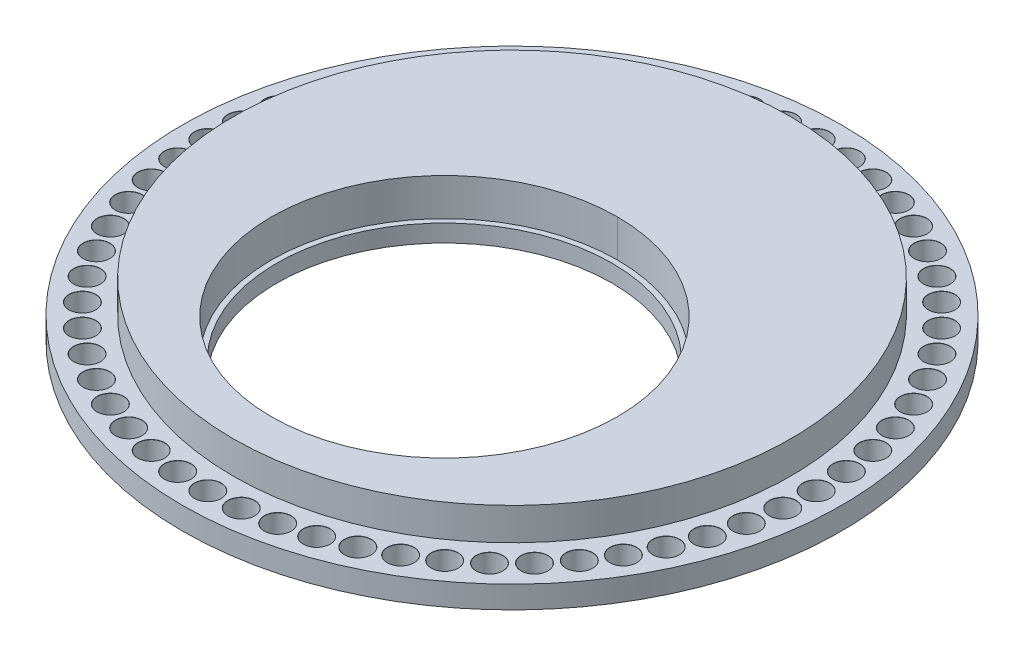
SolidWorks part; units mm, degrees
material "6061-T6 (SS)"
ref_plane "X-Y Datum" through (0, 0, 0) normal (0, 0, 1) x (1, 0, 0)
ref_plane "X-Z Datum" through (0, 0, 0) normal (0, 1, 0) x (1, 0, 0)
ref_plane "Y-Z Datum" through (0, 0, 0) normal (1, 0, 0) x (0, 0, -1)
sketch "Sketch1" plane through (0, 0, 0) normal (0, 1, 0) x (1, 0, 0)
  line L0 (0, 0) -> (0, -12.7) construction
  line L1 (0, -43.0151) -> (0, 43.0151) construction
  line L2 (0, 52.3875) -> (0, 61.9125) construction
  circle A0 centre (0, -12.7) radius 30.988
  circle A1 centre (0, 0) radius 52.3875 construction
  circle A2 centre (0, 0) radius 61.9125
  circle A3 centre (0, 0) radius 57.15 construction
  point P12 (0, 57.15)
  dimension "D2" = 61.976
  dimension "D3" = 104.775
  dimension "D4" = 123.825
  dimension "D5" = 114.3
  dimension "D1" = 12.7
extrude "Slotted-Body Extrude" add sketch "Sketch1" along normal blind 4.191
sketch "Sketch5" plane through (0, 4.191, 0) normal (0, 1, 0) x (1, 0, 0)
  circle A0 centre (0, 0) radius 52.3875 construction
  circle A1 centre (0, 0) radius 52.3875
extrude "Boss-Extrude3" add sketch "Sketch5" along normal blind 6.08
sketch "Sketch6" plane through (0, 0, 0) normal (0, -1, 0) x (1, 0, 0)
  line L0 (0, 73.8452) -> (0, -27.2688) construction
  line L1 (0, -27.2688) -> (0, -30.4713) construction
  line L2 (0, -30.4713) -> (0, -33.9346) construction
  line L3 (0, -46.4199) -> (0, -77.5412) construction
  circle A0 centre (0, 12.7) radius 30.988 construction
  circle A1 centre (0, 12.7) radius 30.988 construction
  circle A2 centre (0, 12.7) radius 32.512
  point P30 (0, 0)
  point P32 (0, 0)
  dimension "D1" = 65.024
extrude "Cut-Extrude5" cut sketch "Sketch6" against normal through all
sketch "Sketch8" plane through (0, 0, 0) normal (0, -1, 0) x (1, 0, 0)
  circle A0 centre (0, 12.7) radius 32.512 construction
  circle A1 centre (0, 12.7) radius 32.512
  circle A2 centre (0, 12.7) radius 31.496
  dimension "D1" = 62.992
extrude "Boss-Extrude4" add sketch "Sketch8" against normal blind 3.255 separate body
hole_wizard "Ø5.0mm Dowel Hole1" positions "Sketch9" profile "Sketch10" hole size "Ø5.0" standard "ANSI Metric" end condition through all
sketch "Sketch9" plane through (0, 4.191, 0) normal (0, 1, 0) x (1, 0, 0)
  point P0 (0, 57.15)
sketch "Sketch10" plane through (0, 4.191, -57.15) normal (1, 0, 0) x (0, 0, 1)
  line L0 (0, 0) -> (0, 4.191)
  line L1 (0, 4.191) -> (2.5, 4.191)
  line L2 (2.5, 4.191) -> (2.5, 0.025)
  line L3 (2.5, 0.025) -> (2.525, 0)
  line L5 (2.525, 0) -> (0, 0)
  line L6 (-2.5, 0.025) -> (-2.525, 0) construction
  line L11 (0, -6.35) -> (0, 107.95) construction
  dimension "Thru Hole Dia." = 5
  dimension "Thru Hole Depth" = 4.191
  dimension "Near C'Sink Dia." = 5.05
  dimension "Near C'Sink Angle" = 90
pattern_circular "CirPattern1" count 60 over 360 about axis through (0, 0, 0) along (0, 1, 0) of "Ø5.0mm Dowel Hole1"
ref_point "Point1"
ref_plane "Plane1" through (0, 0, 0) normal (1, 0, 0) x (0, 0, -1)
split line "Split Line1"
